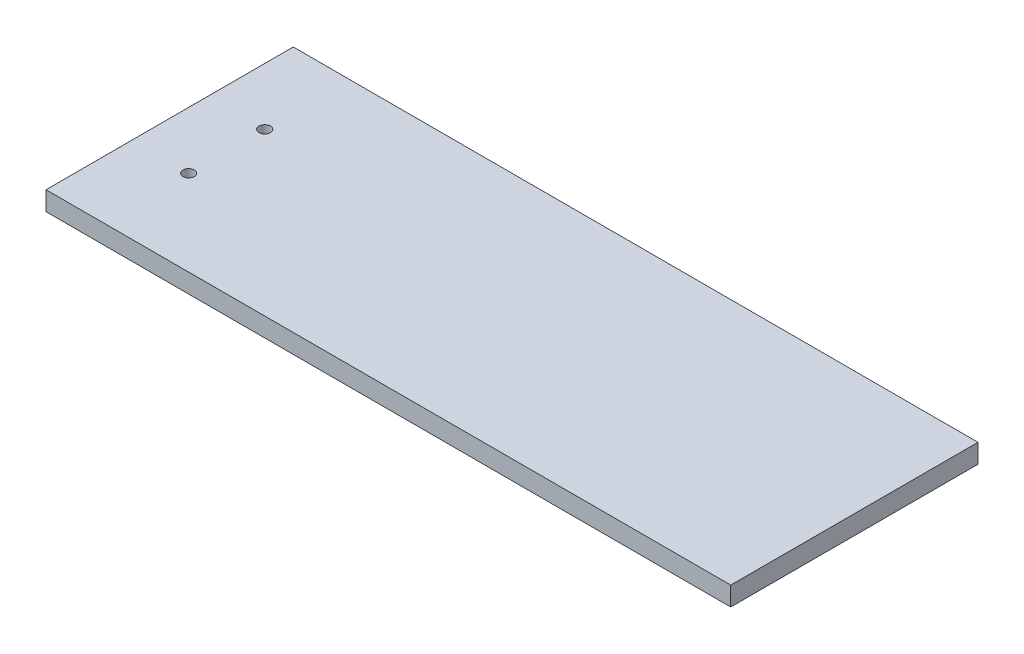
SolidWorks part; units mm, degrees
ref_plane "Front Plane" through (0, 0, 0) normal (0, 0, 1) x (1, 0, 0)
ref_plane "Top Plane" through (0, 0, 0) normal (0, 1, 0) x (1, 0, 0)
ref_plane "Right Plane" through (0, 0, 0) normal (1, 0, 0) x (0, 0, -1)
sketch "Sketch1" plane through (0, 0, 0) normal (0, 1, 0) x (1, 0, 0)
  line L1 (-77.0192, -35.7212) -> (102.9808, -35.7212)
  line L2 (-77.0192, -35.7212) -> (-77.0192, 29.2788)
  line L3 (-77.0192, 29.2788) -> (102.9808, 29.2788)
  line L4 (102.9808, -35.7212) -> (102.9808, 29.2788)
  line L5 (-77.0192, -35.7212) -> (102.9808, 29.2788) construction
  line L6 (-77.0192, 29.2788) -> (102.9808, -35.7212) construction
  point P0 (12.9808, -3.2212)
  dimension "D1" = 180
  dimension "D2" = 65
extrude "Boss-Extrude1" add sketch "Sketch1" along normal blind 5
sketch "Sketch2" plane through (0, 5, 0) normal (0, 1, 0) x (1, 0, 0)
  line L0 (-77.0192, 29.2788) -> (-77.0192, -35.7212) construction
  line L1 (-77.0192, -35.7212) -> (102.9808, -35.7212) construction
  circle A0 centre (-62.0192, 6.7788) radius 1.5
  circle A1 centre (-62.0192, -13.2212) radius 1.5
  dimension "D2" = 3
  dimension "D3" = 15
  dimension "D4" = 3
  dimension "D5" = 22.5
  dimension "D6" = 15
  dimension "D1" = 22.5
extrude "Cut-Extrude1" cut sketch "Sketch2" against normal through all
